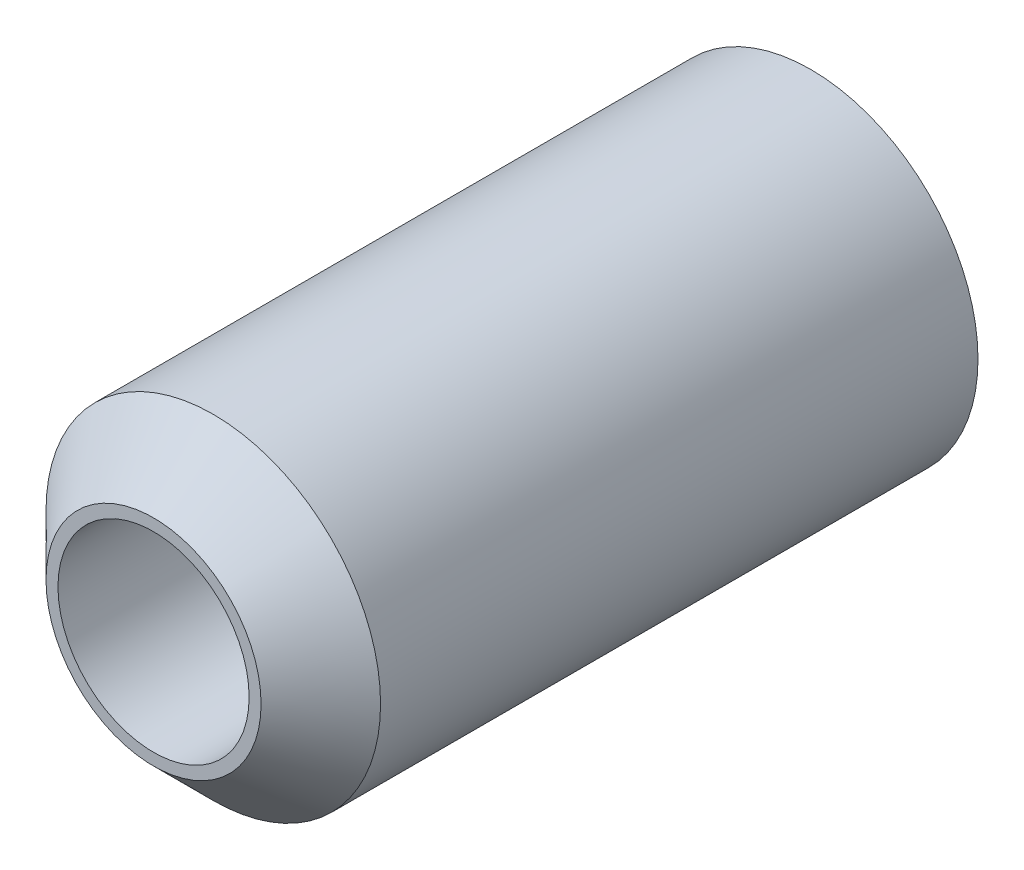
SolidWorks part; units mm, degrees
ref_plane "Front Plane" through (0, 0, 0) normal (0, 0, 1) x (1, 0, 0)
ref_plane "Top Plane" through (0, 0, 0) normal (0, 1, 0) x (1, 0, 0)
ref_plane "Right Plane" through (0, 0, 0) normal (1, 0, 0) x (0, 0, -1)
sketch "Sketch1" plane through (0, 0, 0) normal (0, 0, 1) x (1, 0, 0)
  circle A0 centre (0, 0) radius 1.6
  circle A1 centre (0, 0) radius 2.8
  dimension "D1" = 3.2
  dimension "D2" = 5.6
extrude "Boss-Extrude1" add sketch "Sketch1" along normal blind 11
chamfer "Chamfer1" distance 1 angle 45 1 edges at (2.8, 0, 11)
